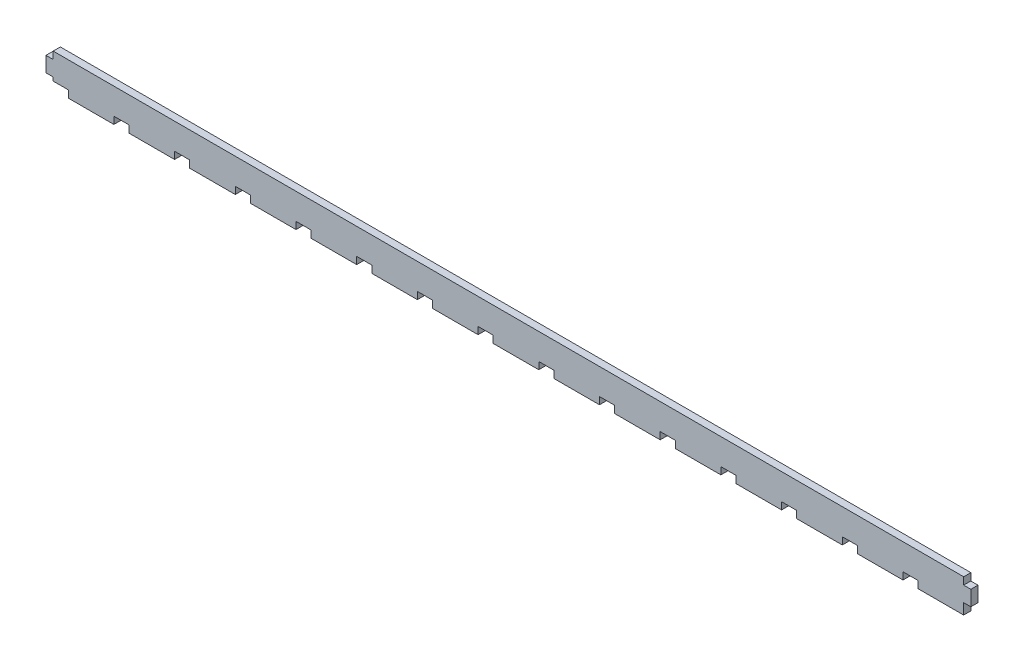
SolidWorks part; units mm, degrees
ref_plane "Front Plane" through (0, 0, 0) normal (0, 0, 1) x (1, 0, 0)
ref_plane "Top Plane" through (0, 0, 0) normal (0, 1, 0) x (1, 0, 0)
ref_plane "Right Plane" through (0, 0, 0) normal (1, 0, 0) x (0, 0, -1)
sketch "Sketch1" plane through (0, 0, 0) normal (0, 0, 1) x (1, 0, 0)
  line L0 (2.9972, -15.875) -> (0, -15.875) construction
  line L1 (0, -15.875) -> (0, -9.525) construction
  line L2 (2.9972, -9.525) -> (0, -9.525) construction
  line L3 (9.3472, -17.3728) -> (9.3472, -20.37) construction
  line L4 (9.3472, -20.37) -> (28.3972, -20.37) construction
  line L5 (28.3972, -17.3728) -> (28.3972, -20.37) construction
  line L6 (34.7472, -17.3728) -> (34.7472, -20.37) construction
  line L7 (34.7472, -20.37) -> (53.7972, -20.37) construction
  line L8 (53.7972, -17.3728) -> (53.7972, -20.37) construction
  line L9 (60.1472, -17.3728) -> (60.1472, -20.37) construction
  line L10 (60.1472, -20.37) -> (79.1972, -20.37) construction
  line L11 (79.1972, -17.3728) -> (79.1972, -20.37) construction
  line L12 (85.5472, -17.3728) -> (85.5472, -20.37) construction
  line L13 (85.5472, -20.37) -> (104.5972, -20.37) construction
  line L14 (104.5972, -17.3728) -> (104.5972, -20.37) construction
  line L15 (110.9472, -17.3728) -> (110.9472, -20.37) construction
  line L16 (110.9472, -20.37) -> (129.9972, -20.37) construction
  line L17 (129.9972, -17.3728) -> (129.9972, -20.37) construction
  line L18 (136.3472, -17.3728) -> (136.3472, -20.37) construction
  line L19 (136.3472, -20.37) -> (155.3972, -20.37) construction
  line L20 (155.3972, -17.3728) -> (155.3972, -20.37) construction
  line L21 (161.7472, -17.3728) -> (161.7472, -20.37) construction
  line L22 (161.7472, -20.37) -> (180.7972, -20.37) construction
  line L23 (180.7972, -17.3728) -> (180.7972, -20.37) construction
  line L24 (187.1472, -17.3728) -> (187.1472, -20.37) construction
  line L25 (187.1472, -20.37) -> (206.1972, -20.37) construction
  line L26 (206.1972, -17.3728) -> (206.1972, -20.37) construction
  line L27 (212.5472, -17.3728) -> (212.5472, -20.37) construction
  line L28 (212.5472, -20.37) -> (231.5972, -20.37) construction
  line L29 (231.5972, -17.3728) -> (231.5972, -20.37) construction
  line L30 (237.9472, -17.3728) -> (237.9472, -20.37) construction
  line L31 (237.9472, -20.37) -> (256.9972, -20.37) construction
  line L32 (256.9972, -17.3728) -> (256.9972, -20.37) construction
  line L33 (263.3472, -17.3728) -> (263.3472, -20.37) construction
  line L34 (263.3472, -20.37) -> (282.3972, -20.37) construction
  line L35 (282.3972, -17.3728) -> (282.3972, -20.37) construction
  line L36 (288.7472, -17.3728) -> (288.7472, -20.37) construction
  line L37 (288.7472, -20.37) -> (307.7972, -20.37) construction
  line L38 (307.7972, -17.3728) -> (307.7972, -20.37) construction
  line L39 (314.1472, -17.3728) -> (314.1472, -20.37) construction
  line L40 (314.1472, -20.37) -> (333.1972, -20.37) construction
  line L41 (333.1972, -17.3728) -> (333.1972, -20.37) construction
  line L42 (339.5472, -17.3728) -> (339.5472, -20.37) construction
  line L43 (339.5472, -20.37) -> (358.5972, -20.37) construction
  line L44 (358.5972, -17.3728) -> (358.5972, -20.37) construction
  line L45 (364.9472, -17.3728) -> (364.9472, -20.37) construction
  line L46 (364.9472, -20.37) -> (383.9972, -20.37) construction
  line L47 (2.9972, -15.875) -> (0, -15.875)
  line L48 (0, -15.875) -> (0, -9.525)
  line L49 (2.9972, -9.525) -> (0, -9.525)
  line L50 (9.3472, -17.3728) -> (9.3472, -20.37)
  line L51 (9.3472, -20.37) -> (28.3972, -20.37)
  line L52 (28.3972, -17.3728) -> (28.3972, -20.37)
  line L53 (34.7472, -17.3728) -> (34.7472, -20.37)
  line L54 (34.7472, -20.37) -> (53.7972, -20.37)
  line L55 (53.7972, -17.3728) -> (53.7972, -20.37)
  line L56 (60.1472, -17.3728) -> (60.1472, -20.37)
  line L57 (60.1472, -20.37) -> (79.1972, -20.37)
  line L58 (79.1972, -17.3728) -> (79.1972, -20.37)
  line L59 (85.5472, -17.3728) -> (85.5472, -20.37)
  line L60 (85.5472, -20.37) -> (104.5972, -20.37)
  line L61 (104.5972, -17.3728) -> (104.5972, -20.37)
  line L62 (110.9472, -17.3728) -> (110.9472, -20.37)
  line L63 (110.9472, -20.37) -> (129.9972, -20.37)
  line L64 (129.9972, -17.3728) -> (129.9972, -20.37)
  line L65 (136.3472, -17.3728) -> (136.3472, -20.37)
  line L66 (136.3472, -20.37) -> (155.3972, -20.37)
  line L67 (155.3972, -17.3728) -> (155.3972, -20.37)
  line L68 (161.7472, -17.3728) -> (161.7472, -20.37)
  line L69 (161.7472, -20.37) -> (180.7972, -20.37)
  line L70 (180.7972, -17.3728) -> (180.7972, -20.37)
  line L71 (187.1472, -17.3728) -> (187.1472, -20.37)
  line L72 (187.1472, -20.37) -> (206.1972, -20.37)
  line L73 (206.1972, -17.3728) -> (206.1972, -20.37)
  line L74 (212.5472, -17.3728) -> (212.5472, -20.37)
  line L75 (212.5472, -20.37) -> (231.5972, -20.37)
  line L76 (231.5972, -17.3728) -> (231.5972, -20.37)
  line L77 (237.9472, -17.3728) -> (237.9472, -20.37)
  line L78 (237.9472, -20.37) -> (256.9972, -20.37)
  line L79 (256.9972, -17.3728) -> (256.9972, -20.37)
  line L80 (263.3472, -17.3728) -> (263.3472, -20.37)
  line L81 (263.3472, -20.37) -> (282.3972, -20.37)
  line L82 (282.3972, -17.3728) -> (282.3972, -20.37)
  line L83 (288.7472, -17.3728) -> (288.7472, -20.37)
  line L84 (288.7472, -20.37) -> (307.7972, -20.37)
  line L85 (307.7972, -17.3728) -> (307.7972, -20.37)
  line L86 (314.1472, -17.3728) -> (314.1472, -20.37)
  line L87 (314.1472, -20.37) -> (333.1972, -20.37)
  line L88 (333.1972, -17.3728) -> (333.1972, -20.37)
  line L89 (339.5472, -17.3728) -> (339.5472, -20.37)
  line L90 (339.5472, -20.37) -> (358.5972, -20.37)
  line L91 (358.5972, -17.3728) -> (358.5972, -20.37)
  line L92 (364.9472, -17.3728) -> (364.9472, -20.37)
  line L93 (364.9472, -20.37) -> (383.9972, -20.37)
  line L94 (2.9972, -15.875) -> (2.9972, -17.3728)
  line L95 (2.9972, -17.3728) -> (9.3472, -17.3728)
  line L96 (28.3972, -17.3728) -> (34.7472, -17.3728)
  line L97 (53.7972, -17.3728) -> (60.1472, -17.3728)
  line L98 (79.1972, -17.3728) -> (85.5472, -17.3728)
  line L99 (104.5972, -17.3728) -> (110.9472, -17.3728)
  line L100 (129.9972, -17.3728) -> (136.3472, -17.3728)
  line L101 (155.3972, -17.3728) -> (161.7472, -17.3728)
  line L102 (180.7972, -17.3728) -> (187.1472, -17.3728)
  line L103 (206.1972, -17.3728) -> (212.5472, -17.3728)
  line L104 (231.5972, -17.3728) -> (237.9472, -17.3728)
  line L105 (256.9972, -17.3728) -> (263.3472, -17.3728)
  line L106 (282.3972, -17.3728) -> (288.7472, -17.3728)
  line L107 (307.7972, -17.3728) -> (314.1472, -17.3728)
  line L108 (333.1972, -17.3728) -> (339.5472, -17.3728)
  line L109 (358.5972, -17.3728) -> (364.9472, -17.3728)
  line L110 (2.9972, -27.0537) -> (383.9972, -27.0537) construction
  line L111 (193.4972, -27.0537) -> (193.4972, 26.369) construction
  line L112 (383.9972, -15.875) -> (383.9972, -17.3728)
  line L113 (383.9972, -9.525) -> (386.9944, -9.525)
  line L114 (386.9944, -15.875) -> (386.9944, -9.525)
  line L115 (383.9972, -15.875) -> (386.9944, -15.875)
  line L116 (383.9972, -17.3728) -> (383.9972, -20.37)
  line L117 (383.9972, -9.525) -> (383.9972, -6.477)
  line L118 (383.9972, -6.477) -> (2.9972, -6.477)
  line L119 (2.9972, 21.005) -> (2.9972, -21.005) construction
  line L120 (2.9972, -6.477) -> (2.9972, -9.525)
  dimension "D1" = 3.048
extrude "Boss-Extrude1" add sketch "Sketch1" along normal blind 2.9972
